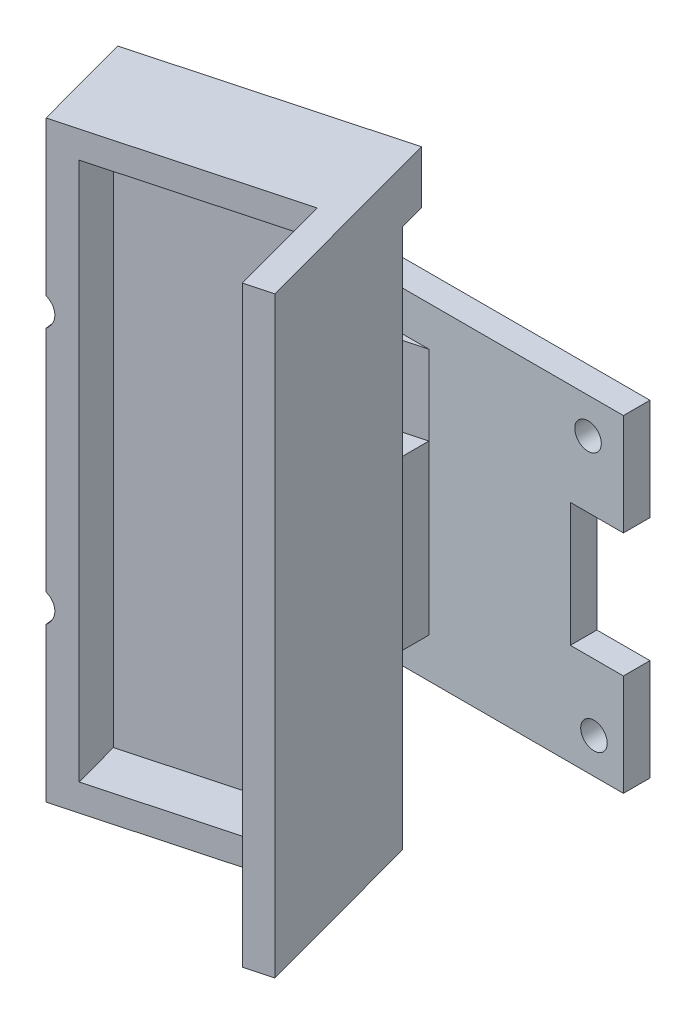
SolidWorks part; units mm, degrees
ref_plane "Alzado" through (0, 0, 0) normal (0, 0, 1) x (1, 0, 0)
ref_plane "Planta" through (0, 0, 0) normal (0, 1, 0) x (1, 0, 0)
ref_plane "Vista lateral" through (0, 0, 0) normal (1, 0, 0) x (0, 0, -1)
sketch "Croquis1" plane through (0, 0, 0) normal (0, 0, 1) x (1, 0, 0)
  line L1 (-65.2968, 25.2877) -> (-13.2968, 25.2877)
  line L2 (-65.2968, 25.2877) -> (-65.2968, -11.7123)
  line L3 (-65.2968, -11.7123) -> (-13.2968, -11.7123)
  line L4 (-13.2968, 25.2877) -> (-13.2968, -11.7123)
  dimension "D1" = 52
  dimension "D2" = 37
extrude "Saliente-Extruir1" add sketch "Croquis1" along normal blind 3
fillet "Redondeo1" radius 3 2 edges at (-65.2968, -11.7123, 1.5) (-65.2968, 25.2877, 1.5)
sketch "Croquis2" plane through (0, 0, 3) normal (0, 0, 1) x (1, 0, 0)
  line L0 (-62.2968, -11.7123) -> (-13.2968, -11.7123) construction
  line L3 (-65.2968, 22.2877) -> (-65.2968, -8.7123) construction
  circle A0 centre (-61.2968, 21.2877) radius 1.5
  circle A1 centre (-61.2968, -7.7123) radius 1.5
  circle A2 centre (-16.6241, -7.7123) radius 1.5
  circle A3 centre (-17.2968, 21.2877) radius 1.5
  dimension "D1" = 29
  dimension "D4" = 29
  dimension "D2" = 4
  dimension "D3" = 4
  dimension "D5" = 44
  dimension "D6" = 4
extrude "Cortar-Extruir1" cut sketch "Croquis2" against normal blind 3
sketch "Croquis3" plane through (0, 0, 3) normal (0, 0, 1) x (1, 0, 0)
  line L0 (-65.2968, 22.2877) -> (-65.2968, -8.7123) construction
  line L1 (-65.2968, 16.7877) -> (-36.2968, 16.7877)
  line L2 (-65.2968, 16.7877) -> (-65.2968, -3.2123)
  line L3 (-65.2968, -3.2123) -> (-36.2968, -3.2123)
  line L4 (-36.2968, 16.7877) -> (-36.2968, -3.2123)
  line L5 (-62.2968, -11.7123) -> (-13.2968, -11.7123) construction
  line L7 (-13.2968, -11.7123) -> (-13.2968, 25.2877) construction
  line L9 (-13.2968, 13.7877) -> (-19.2968, 13.7877)
  line L10 (-13.2968, 13.7877) -> (-13.2968, -0.2123)
  line L11 (-13.2968, -0.2123) -> (-19.2968, -0.2123)
  line L12 (-19.2968, 13.7877) -> (-19.2968, -0.2123)
  dimension "D1" = 29
  dimension "D2" = 20
  dimension "D3" = 8.5
  dimension "D4" = 6
  dimension "D5" = 14
  dimension "D6" = 11.5
extrude "Cortar-Extruir2" cut sketch "Croquis3" against normal blind 3
sketch "Croquis4" plane through (0, 0, 3) normal (0, 0, 1) x (1, 0, 0)
  line L0 (-57.2968, 16.7877) -> (-57.2968, 20.7902)
  line L1 (-36.2968, 16.7877) -> (-65.2968, 16.7877) construction
  line L2 (-57.2968, 20.7902) -> (-26.2968, 20.7902)
  line L3 (-26.2968, 20.7902) -> (-26.2968, -7.2123)
  line L4 (-26.2968, -7.2123) -> (-57.2968, -7.2123)
  line L5 (-57.2968, -7.2123) -> (-57.2968, -3.2123)
  line L6 (-65.2968, -3.2123) -> (-36.2968, -3.2123) construction
  line L7 (-57.2968, -3.2123) -> (-36.2968, -3.2123)
  line L8 (-36.2968, -3.2123) -> (-36.2968, 16.7877)
  line L9 (-36.2968, 16.7877) -> (-57.2968, 16.7877)
  line L10 (-65.2968, 22.2877) -> (-65.2968, 16.7877) construction
  line L11 (-65.2968, -3.2123) -> (-65.2968, -8.7123) construction
  dimension "D1" = 4
  dimension "D2" = 10
  dimension "D3" = 4.0026
  dimension "D4" = 8
  dimension "D5" = 8
extrude "Saliente-Extruir2" add sketch "Croquis4" along normal blind 9
sketch "Croquis5" plane through (0, 0, 12) normal (0, 0, 1) x (1, 0, 0)
  line L1 (-26.2968, 20.7902) -> (-62.2968, 20.7902)
  line L2 (-26.2968, 20.7902) -> (-26.2968, -7.2123)
  line L3 (-26.2968, -7.2123) -> (-62.2968, -7.2123)
  line L4 (-62.2968, 20.7902) -> (-62.2968, -7.2123)
  dimension "D1" = 28.0026
  dimension "D2" = 36
extrude "Saliente-Extruir3" add sketch "Croquis5" along normal blind 10.3
sketch "Croquis6" plane through (0, -7.2123, 0) normal (0, -1, 0) x (1, 0, 0)
  line L0 (-35.2968, 15) -> (-35.2968, 12.9954)
  line L2 (-35.2968, 12.9954) -> (-26.2968, 12.9954)
  line L3 (-35.2968, 15) -> (-62.2968, 22.3)
  line L6 (-26.2968, 22.3) -> (-26.2968, 3) construction
  line L7 (-26.2968, 14.7574) -> (-26.2968, 22.3)
  line L8 (-26.2968, 22.3) -> (-62.2968, 22.3)
  line L9 (-26.2968, 12.9954) -> (-26.2968, 14.7574)
extrude "Cortar-Extruir3" cut sketch "Croquis6" against normal up to vertex
sketch "Croquis7" plane through (1.3749, 0, 5.0851) normal (0.261, 0, 0.9653) x (0.9653, 0, -0.261)
  line L0 (-65.9578, 6.7889) -> (-65.9578, -26.7111)
  line L1 (-65.9578, 20.7902) -> (-65.9578, -7.2123) construction
  line L2 (-65.9578, -26.7111) -> (-37.9578, -26.7111)
  line L3 (-37.9578, -26.7111) -> (-37.9578, 40.2889)
  line L4 (-37.9578, 40.2889) -> (-65.9578, 40.2889)
  line L5 (-65.9578, 40.2889) -> (-65.9578, 6.7889)
  dimension "D1" = 28
  dimension "D2" = 67
  dimension "D3" = 33.5
  dimension "D4" = 33.5
extrude "Saliente-Extruir4" add sketch "Croquis7" along normal blind 8.5
sketch "Croquis8" plane through (3.5933, 0, 13.2905) normal (0.261, 0, 0.9653) x (0.9653, 0, -0.261)
  line L0 (-65.9578, -26.7111) -> (-37.9578, -26.7111) construction
  line L1 (-62.9078, -23.6611) -> (-41.0078, -23.6611)
  line L2 (-62.9078, -23.6611) -> (-62.9078, 37.2389)
  line L3 (-62.9078, 37.2389) -> (-41.0078, 37.2389)
  line L4 (-41.0078, -23.6611) -> (-41.0078, 37.2389)
  line L5 (-37.9578, 40.2889) -> (-65.9578, 40.2889) construction
  line L6 (-65.9578, 40.2889) -> (-65.9578, -26.7111) construction
  line L7 (-37.9578, -26.7111) -> (-37.9578, 40.2889) construction
  dimension "D1" = 3.05
  dimension "D2" = 3.05
  dimension "D3" = 3.05
  dimension "D4" = 3.05
extrude "Cortar-Extruir4" cut sketch "Croquis8" against normal blind 5.5
sketch "Croquis10" plane through (0, 20.7902, 0) normal (0, 1, 0) x (1, 0, 0)
  line L0 (-62.2968, -22.3) -> (-35.2968, -15)
  line L1 (-35.2968, -15) -> (-35.2968, -12)
  line L2 (-35.2968, -12) -> (-62.2968, -19.3)
  line L3 (-62.2968, -22.3) -> (-62.2968, -12) construction
  line L4 (-62.2968, -19.3) -> (-62.2968, -22.3)
extrude "Cortar-Extruir5" cut sketch "Croquis10" against normal blind 9
sketch "Croquis12" plane through (0, 20.7902, 0) normal (0, 1, 0) x (1, 0, 0)
  line L0 (-26.2968, -12.9954) -> (-35.2968, -12.9954)
  line L1 (-26.2968, -12.9954) -> (-26.2968, -11.4245)
  line L2 (-26.2968, -12.9954) -> (-26.2968, -3) construction
  line L4 (-26.2968, -11.4245) -> (-35.2968, -11.4245)
  line L5 (-35.2968, -11.4245) -> (-35.2968, -12.9954)
extrude "Cortar-Extruir6" cut sketch "Croquis12" against normal up to vertex
sketch "Croquis13" plane through (3.5933, 0, 13.2905) normal (0.261, 0, 0.9653) x (0.9653, 0, -0.261)
  line L0 (-37.9578, 40.2889) -> (-65.9578, 40.2889) construction
  line L1 (-37.9578, -26.7111) -> (-40.9578, -26.7111)
  line L2 (-37.9578, -26.7111) -> (-37.9578, 40.2889)
  line L3 (-37.9578, 40.2889) -> (-40.9578, 40.2889)
  line L4 (-40.9578, -26.7111) -> (-40.9578, 40.2889)
extrude "Saliente-Extruir5" add sketch "Croquis13" along normal blind 12
sketch "Croquis14" plane through (0, -7.2123, 0) normal (0, -1, 0) x (1, 0, 0)
  line L1 (-57.2968, 12) -> (-26.2968, 12)
  line L2 (-57.2968, 12) -> (-57.2968, 3)
  line L3 (-57.2968, 3) -> (-26.2968, 3)
  line L4 (-26.2968, 12) -> (-26.2968, 3)
extrude "Cortar-Extruir7" cut sketch "Croquis14" against normal up to vertex
sketch "Croquis17" plane through (0, 0, 3) normal (0, 0, 1) x (1, 0, 0)
  line L0 (-13.2968, -0.2123) -> (-19.2968, -0.2123)
  line L1 (-19.2968, -0.2123) -> (-19.2968, 13.7877)
  line L2 (-19.2968, 13.7877) -> (-13.2968, 13.7877)
  line L3 (-13.2968, 13.7877) -> (-13.2968, 25.2877)
  line L4 (-13.2968, 25.2877) -> (-62.2968, 25.2877)
  line L5 (-65.2968, 22.2877) -> (-65.2968, 16.7877)
  line L7 (-65.2968, 16.7877) -> (-36.2968, 16.7877)
  line L8 (-36.2968, 16.7877) -> (-36.2968, -3.2123)
  line L9 (-36.2968, -3.2123) -> (-65.2968, -3.2123)
  line L10 (-65.2968, -3.2123) -> (-65.2968, -8.7123)
  line L11 (-62.2968, -11.7123) -> (-13.2968, -11.7123)
  line L12 (-13.2968, -11.7123) -> (-13.2968, -0.2123)
  arc A0 (-62.2968, -11.7123) -> (-65.2968, -8.7123) centre (-62.2968, -8.7123) cw
  arc A1 (-65.2968, 22.2877) -> (-62.2968, 25.2877) centre (-62.2968, 22.2877) cw
  circle A2 centre (-61.2968, 21.2877) radius 1.5
  circle A3 centre (-61.2968, -7.7123) radius 1.5
  circle A4 centre (-16.6241, -7.7123) radius 1.5
  circle A5 centre (-17.2968, 21.2877) radius 1.5
extrude "Saliente-Extruir6" add sketch "Croquis17" along normal up to vertex (9 mm away)
sketch "Croquis18" plane through (0, -11.7123, 0) normal (0, -1, 0) x (1, 0, 0)
  line L1 (-13.2968, 0) -> (-67.494, 0)
  line L2 (-13.2968, 0) -> (-13.2968, 9)
  line L3 (-13.2968, 9) -> (-67.494, 9)
  line L4 (-67.494, 0) -> (-67.494, 9)
  dimension "D1" = 9
extrude "Cortar-Extruir8" cut sketch "Croquis18" against normal up to vertex
sketch "Croquis19" plane through (0, 0, 9) normal (0, 0, -1) x (-1, 0, 0)
  circle A0 centre (61.2968, 21.2877) radius 1.5
  circle A1 centre (61.2968, -7.7123) radius 1.5
extrude "Cortar-Extruir9" cut sketch "Croquis19" against normal up to vertex
sketch "Croquis20" plane through (1.3749, 0, 5.0851) normal (-0.261, 0, -0.9653) x (-0.9653, 0, 0.261)
  line L0 (37.9578, -26.7111) -> (37.9578, 40.2889) construction
  line L1 (65.9578, 40.2889) -> (37.9578, 40.2889)
  line L2 (65.9578, 40.2889) -> (65.9578, 34.2889)
  line L3 (65.9578, 34.2889) -> (37.9578, 34.2889)
  line L4 (37.9578, 40.2889) -> (37.9578, 34.2889)
  dimension "D1" = 6
extrude "Saliente-Extruir7" add sketch "Croquis20" along normal blind 3
sketch "Croquis21" plane through (0, 0, 9) normal (0, 0, -1) x (-1, 0, 0)
  line L0 (65.2968, 16.7877) -> (36.2968, 16.7877) construction
  line L1 (55.2968, 16.7877) -> (35.2968, 16.7877)
  line L2 (55.2968, 16.7877) -> (55.2968, 21.2877)
  line L3 (55.2968, 21.2877) -> (35.2968, 21.2877)
  line L4 (35.2968, 16.7877) -> (35.2968, 21.2877)
  line L5 (36.2968, -3.2123) -> (65.2968, -3.2123) construction
  line L6 (55.2968, -3.2123) -> (35.2968, -3.2123)
  line L7 (55.2968, -3.2123) -> (55.2968, -7.7123)
  line L8 (55.2968, -7.7123) -> (35.2968, -7.7123)
  line L9 (35.2968, -3.2123) -> (35.2968, -7.7123)
  line L10 (13.2968, 25.2877) -> (62.2968, 25.2877) construction
  line L11 (13.2968, -11.7123) -> (62.2968, -11.7123) construction
  line L12 (65.2968, 22.2877) -> (65.2968, 16.7877) construction
  line L13 (65.2968, -3.2123) -> (65.2968, -8.7123) construction
  dimension "D1" = 4
  dimension "D2" = 4
  dimension "D3" = 10
  dimension "D4" = 10
  dimension "D5" = 20
  dimension "D6" = 20
extrude "Cortar-Extruir10" cut sketch "Croquis21" against normal blind 2
sketch "Croquis22" plane through (0, 0, 12) normal (0, 0, 1) x (1, 0, 0)
  circle A0 centre (-61.2968, 21.2877) radius 3
  circle A1 centre (-61.2968, -7.7123) radius 3
extrude "Cortar-Extruir11" cut sketch "Croquis22" along normal up to vertex (10.3 mm away)
sketch "Croquis23" plane through (0, 0, 12) normal (0, 0, 1) x (1, 0, 0)
  circle A0 centre (-61.2968, 21.2877) radius 2
  circle A1 centre (-61.2968, -7.7123) radius 2
extrude "Cortar-Extruir12" cut sketch "Croquis23" along normal up to vertex
